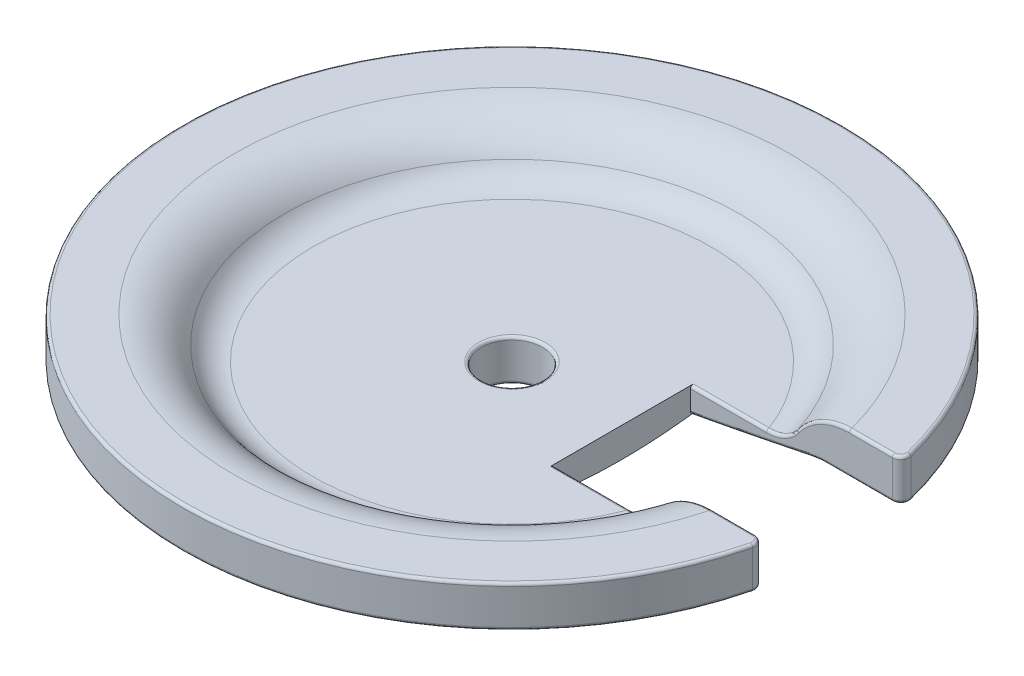
SolidWorks part; units mm, degrees
ref_plane "Front Plane" through (0, 0, 0) normal (0, 0, 1) x (1, 0, 0)
ref_plane "Top Plane" through (0, 0, 0) normal (0, 1, 0) x (1, 0, 0)
ref_plane "Right Plane" through (0, 0, 0) normal (1, 0, 0) x (0, 0, -1)
sketch "Sketch1" plane through (0, 0, 0) normal (0, 0, 1) x (1, 0, 0)
  line L0 (0, 0) -> (48.4, 0) construction
  line L1 (4.4925, 0) -> (7.0141, 0)
  line L2 (9.5493, 0.2686) -> (35.2773, 5.7814)
  line L3 (37.8125, 6.05) -> (48.4, 6.05)
  line L4 (4.4925, 0) -> (4.4925, 6.05)
  line L5 (4.4925, 6.05) -> (29.2409, 6.05)
  line L6 (40.8253, 12.1) -> (48.4, 12.1)
  line L7 (48.4, 12.1) -> (48.4, 6.05)
  line L8 (0, 0) -> (0, 12.9961) construction
  arc A0 (7.0141, 0) -> (9.5493, 0.2686) centre (7.0141, 12.1) ccw
  arc A1 (35.2773, 5.7814) -> (37.8125, 6.05) centre (37.8125, -6.05) cw
  arc A2 (29.2409, 6.05) -> (33.3777, 8.2105) centre (29.2409, 11.0909) ccw
  arc A3 (33.3777, 8.2105) -> (40.8253, 12.1) centre (40.8253, 3.025) cw
  point P3 (4.4925, 0)
  dimension "D4" = 12.1
  dimension "D9" = 5.0409
  dimension "D10" = 9.075
  dimension "D1" = 48.4
  dimension "D2" = 4.4925
  dimension "D3" = 6.05
  dimension "D5" = 2.5216
  dimension "D6" = 10.5875
  dimension "D7" = 6.05
  dimension "D8" = 29.2409
revolve "Revolve1" add sketch "Sketch1" angle 360 about L8
sketch "Sketch2" plane through (0, 12.1, 0) normal (0, 1, 0) x (1, 0, 0)
  line L1 (66.55, 10.0833) -> (16.1333, 10.0833)
  line L2 (66.55, 10.0833) -> (66.55, -10.0833)
  line L3 (66.55, -10.0833) -> (16.1333, -10.0833)
  line L4 (16.1333, 10.0833) -> (16.1333, -10.0833)
  point P4 (16.1333, 0)
  dimension "D1" = 20.1667
  dimension "D2" = 50.4167
  dimension "D3" = 16.1333
extrude "Cut-Extrude1" cut sketch "Sketch2" against normal through all
fillet "Fillet1" radius 1.25 2 edges at (47.338, 9.075, 10.0833) (47.338, 9.075, -10.0833)
fillet "Fillet2" radius 0.42 22 edges at (21.7903, 6.05, 10.0833) (28.4746, 6.1435, 10.0833) (44.6001, -4.6131, 10.0833) (42.6641, 12.1, 10.0833) (46.752, 12.1, 10.563) (21.7903, 6.05, -10.0833) (31.1749, 7.4867, -10.0833) (42.7501, -5.5049, -10.0833) (42.6641, 12.1, -10.0833) (46.752, 12.1, -10.563) (41.1055, 6.05, 10.0833) (46.752, 6.05, 10.563) (41.1055, 6.05, -10.0833) (46.752, 6.05, -10.563) (0, 6.05, -4.4925) (0, 0, -4.4925) (-48.4, 12.1, 0) (-48.4, 6.05, 0)
ref_plane "Plane1" through (0, 0, 0) normal (0, -1, 0) x (-1, 0, 0)
sketch "Sketch3" plane through (0, 6.05, 0) normal (0, -1, 0) x (1, 0, 0)
  point P0 (0, 0)
equation "\"Lower_Mount_piston_rod_radius\"\t=3.4925"
equation "\"Upper_Mount_largest_radius\" =26.6"
equation "\"Upper_mount_wall_thickness\" =4"
equation "\"Lower_Mount_piston_rod_length\" =149"
equation "\"Piston_orifice_dia\"=0.30711"
equation "\"Spring_inner_dia\" =80"
equation "\"Spring_wire_dia\" =8"
equation "\"D1@Sketch1\"=((\"Spring_inner_dia\"+\"Spring_wire_dia\")/2)*1.1"
equation "\"D5@Sketch1\"=\"D1@Sketch1\"*0.0521"
equation "\"D3@Sketch1\"=\"D1@Sketch1\"/8"
equation "\"D8@Sketch1\"=\"D1@Sketch1\"/1.65521807"
equation "\"D9@Sketch1\"=\"D1@Sketch1\"/9.60153625"
equation "\"D10@Sketch1\"=\"D1@Sketch1\"/5.33333333333333333333"
equation "\"D4@Sketch1\"=\"D1@Sketch1\"/4"
equation "\"D6@Sketch1\"=\"D1@Sketch1\"/4.57142857"
equation "\"D7@Sketch1\"=\"D1@Sketch1\"/8"
equation "\"D1@Sketch2\"=((\"Spring_inner_dia\"+\"Spring_wire_dia\")/2)*1.1/2.4"
equation "\"D2@Sketch2\"=((\"Spring_inner_dia\"+\"Spring_wire_dia\")/2)*1.1/0.96"
equation "\"D2@Sketch1\"=\"Lower_Mount_piston_rod_radius\"+1mm"
equation "\"D3@Sketch2\"=(((\"Spring_inner_dia\"+\"Spring_wire_dia\")/2)*1.1)/3"
